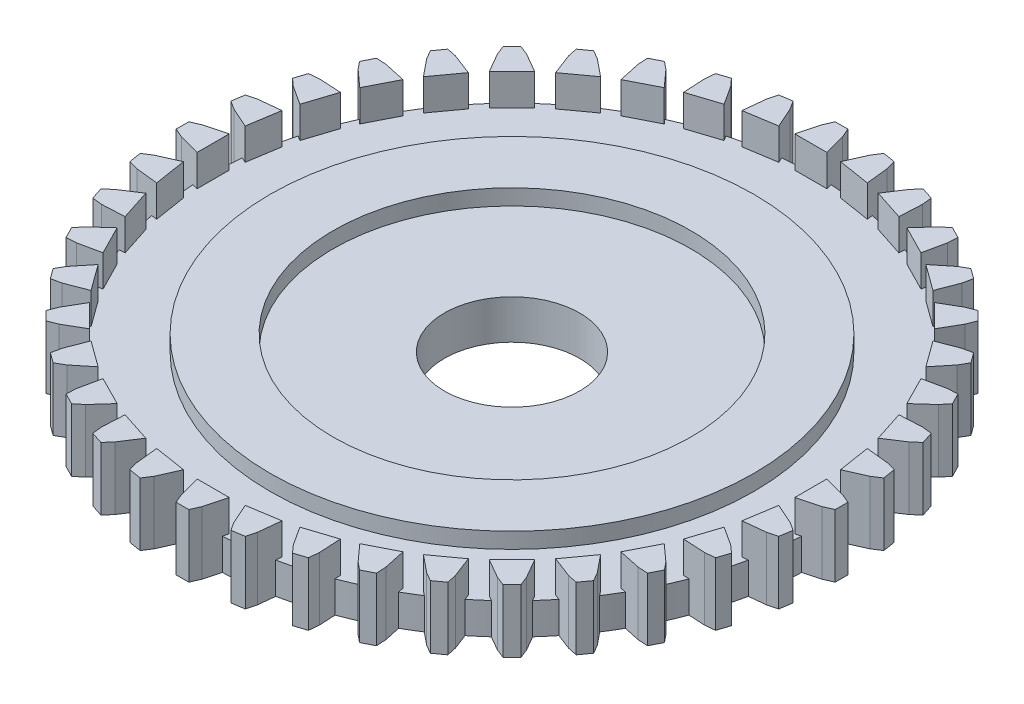
SolidWorks part; units mm, degrees
ref_plane "Front Plane" through (0, 0, 0) normal (0, 0, 1) x (1, 0, 0)
ref_plane "Top Plane" through (0, 0, 0) normal (0, 1, 0) x (1, 0, 0)
ref_plane "Right Plane" through (0, 0, 0) normal (1, 0, 0) x (0, 0, -1)
sketch "Sketch1" plane through (0, 0, 0) normal (0, 1, 0) x (1, 0, 0)
  line L0 (-3.2436, 20.95) -> (3.5044, 20.95) construction
  line L1 (-1.0225, 19) -> (-0.6553, 20.3704)
  line L2 (-0.5, 20.95) -> (0.5, 20.95) construction
  line L3 (0.6553, 20.3704) -> (1.0225, 19)
  line L4 (1.0225, 19) -> (-1.0225, 19)
  line L5 (0.4, 20.95) -> (-0.4, 20.95)
  line L6 (0.6553, 20.3704) -> (0.4, 20.95)
  line L7 (-0.6553, 20.3704) -> (-0.4, 20.95)
  circle A0 centre (0, 0) radius 4.3 construction
  circle A1 centre (0, 0) radius 19.3723 construction
  point P8 (0, 20.95)
  point P11 (0, 19)
  point P14 (0.9287, 19.35)
  dimension "D1" = 8.6
  dimension "D2" = 1.6
  dimension "D3" = 20.95
  dimension "D4" = 1
  dimension "D5" = 75
  dimension "D6" = 19
  dimension "D7" = 0.1
  dimension "D8" = 0.6
  dimension "D9" = 0.6
  dimension "D10" = 0.1
sketch "Sketch2" plane through (0, 0, 0) normal (0, 1, 0) x (1, 0, 0)
  circle A0 centre (0, 0) radius 19.3723
  circle A1 centre (0, 0) radius 4.3
  dimension "D1" = 38.7445
  dimension "D2" = 8.6
extrude "Boss-Extrude1" add sketch "Sketch2" along normal blind 2
extrude "Boss-Extrude2" add sketch "Sketch1" along normal blind 4
pattern_circular "CirPattern1" count 40 over 360 about axis through (0, 0, 0) along (0, 1, 0) of "Boss-Extrude2"
sketch "Sketch3" plane through (0, 2, 0) normal (0, 1, 0) x (1, 0, 0)
  circle A0 centre (0, 0) radius 7.5
  circle A1 centre (0, 0) radius 4.3
  circle A2 centre (0, 0) radius 4.3 construction
  dimension "D1" = 15
extrude "Boss-Extrude3" add sketch "Sketch3" along normal blind 0.5 and the other way offset from surface (2.5 mm away) 0.5 other way up to face at (0, 0, 0)
sketch "Sketch4" plane through (0, 2.5, 0) normal (0, 1, 0) x (1, 0, 0)
  circle A0 centre (0, 0) radius 4.3 construction
  circle A1 centre (0, 0) radius 7.5
  circle A2 centre (0, 0) radius 7.5
  circle A3 centre (0, 0) radius 4.3
  dimension "D1" = 0
extrude "Cut-Extrude1" cut sketch "Sketch4" against normal up to surface (0.5 mm away) up to face at (0, 2, 7.5)
sketch "Sketch5" plane through (0, 2, 0) normal (0, 1, 0) x (1, 0, 0)
  circle A0 centre (0, 0) radius 11.3723
  circle A1 centre (0, 0) radius 15.3723
  arc A2 (16.2004, -10.6223) -> (16.8193, -9.6122) centre (0, 0) ccw construction
  dimension "D1" = 4
  dimension "D2" = 4
extrude "Boss-Extrude4" add sketch "Sketch5" along normal blind 1 and the other way blind 2.5
